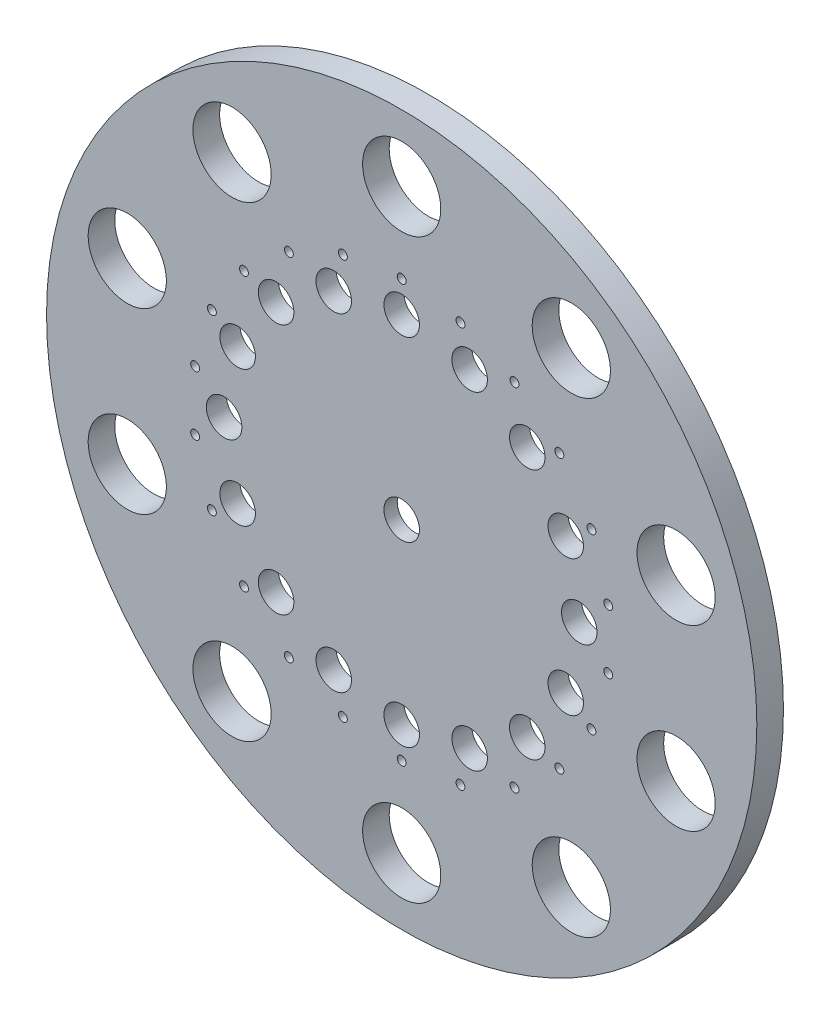
SolidWorks part; units mm, degrees
ref_plane "Front Plane" through (0, 0, 0) normal (0, 0, 1) x (1, 0, 0)
ref_plane "Top Plane" through (0, 0, 0) normal (0, 1, 0) x (1, 0, 0)
ref_plane "Right Plane" through (0, 0, 0) normal (1, 0, 0) x (0, 0, -1)
sketch "Sketch1" plane through (0, 0, 0) normal (0, 0, 1) x (1, 0, 0)
  circle A0 centre (0, 0) radius 80
  point P3 (0, 0)
extrude "Boss-Extrude1" add sketch "Sketch1" along normal blind 6 contours A0
sketch "Sketch2" plane through (0, 0, 0) normal (0, 0, -1) x (-1, 0, 0)
  circle A0 centre (0, 0) radius 20
extrude "Cut-Extrude1" cut sketch "Sketch2" against normal blind 3
sketch "Sketch3" plane through (0, 0, 0) normal (0, 0, -1) x (-1, 0, 0)
  line L0 (0, 20) -> (0, 80) construction
  circle A0 centre (0, 0) radius 20 construction
  circle A1 centre (0, 0) radius 80 construction
  circle A2 centre (0, 65) radius 8.8103
  circle A3 centre (38.206, 52.5861) radius 8.8103
  circle A4 centre (61.8187, 20.0861) radius 8.8103
  circle A5 centre (61.8187, -20.0861) radius 8.8103
  circle A6 centre (38.206, -52.5861) radius 8.8103
  circle A7 centre (0, -65) radius 8.8103
  circle A8 centre (-38.206, -52.5861) radius 8.8103
  circle A9 centre (-61.8187, -20.0861) radius 8.8103
  circle A10 centre (-61.8187, 20.0861) radius 8.8103
  circle A11 centre (-38.206, 52.5861) radius 8.8103
  point P29 (0, 0)
  dimension "D1" = 45
extrude "Cut-Extrude3" cut sketch "Sketch3" against normal blind 6
sketch "Sketch5" plane through (0, 0, 0) normal (0, 0, -1) x (-1, 0, 0)
  circle A0 centre (0, 0) radius 50
extrude "Cut-Extrude5" cut sketch "Sketch5" against normal blind 1.5
sketch "Sketch6" plane through (0, 0, 1.5) normal (0, 0, -1) x (-1, 0, 0)
  line L0 (0, 20) -> (0, 50) construction
  circle A0 centre (0, 0) radius 20 construction
  circle A1 centre (0, 0) radius 20 construction
  circle A2 centre (0, 0) radius 50 construction
  circle A3 centre (0, 47) radius 1
  circle A4 centre (13.2414, 45.0962) radius 1
  circle A5 centre (25.4101, 39.5389) radius 1
  circle A6 centre (35.5202, 30.7785) radius 1
  circle A7 centre (42.7527, 19.5245) radius 1
  circle A8 centre (46.5216, 6.6888) radius 1
  circle A9 centre (46.5216, -6.6888) radius 1
  circle A10 centre (42.7527, -19.5245) radius 1
  circle A11 centre (35.5202, -30.7785) radius 1
  circle A12 centre (25.4101, -39.5389) radius 1
  circle A13 centre (13.2414, -45.0962) radius 1
  circle A14 centre (0, -47) radius 1
  circle A15 centre (-13.2414, -45.0962) radius 1
  circle A16 centre (-25.4101, -39.5389) radius 1
  circle A17 centre (-35.5202, -30.7785) radius 1
  circle A18 centre (-42.7527, -19.5245) radius 1
  circle A19 centre (-46.5216, -6.6888) radius 1
  circle A20 centre (-46.5216, 6.6888) radius 1
  circle A21 centre (-42.7527, 19.5245) radius 1
  circle A22 centre (-35.5202, 30.7785) radius 1
  circle A23 centre (-25.4101, 39.5389) radius 1
  circle A24 centre (-13.2414, 45.0962) radius 1
  circle A25 centre (0, 40) radius 4
  circle A26 centre (15.3073, 36.9552) radius 4
  circle A27 centre (28.2843, 28.2843) radius 4
  circle A28 centre (36.9552, 15.3073) radius 4
  circle A29 centre (40, 0) radius 4
  circle A30 centre (36.9552, -15.3073) radius 4
  circle A31 centre (28.2843, -28.2843) radius 4
  circle A32 centre (15.3073, -36.9552) radius 4
  circle A33 centre (0, -40) radius 4
  circle A34 centre (-15.3073, -36.9552) radius 4
  circle A35 centre (-28.2843, -28.2843) radius 4
  circle A36 centre (-36.9552, -15.3073) radius 4
  circle A37 centre (-40, 0) radius 4
  circle A38 centre (-36.9552, 15.3073) radius 4
  circle A39 centre (-28.2843, 28.2843) radius 4
  circle A40 centre (-15.3073, 36.9552) radius 4
  point P55 (0, 0)
  point P89 (0, 0)
extrude "Cut-Extrude6" cut sketch "Sketch6" against normal blind 6
sketch "Sketch7" plane through (0, 0, 3) normal (0, 0, -1) x (-1, 0, 0)
  circle A0 centre (0, 0) radius 4
  circle A1 centre (0, 0) radius 5
extrude "Cut-Extrude8" cut sketch "Sketch7" against normal blind 6 contours A0
